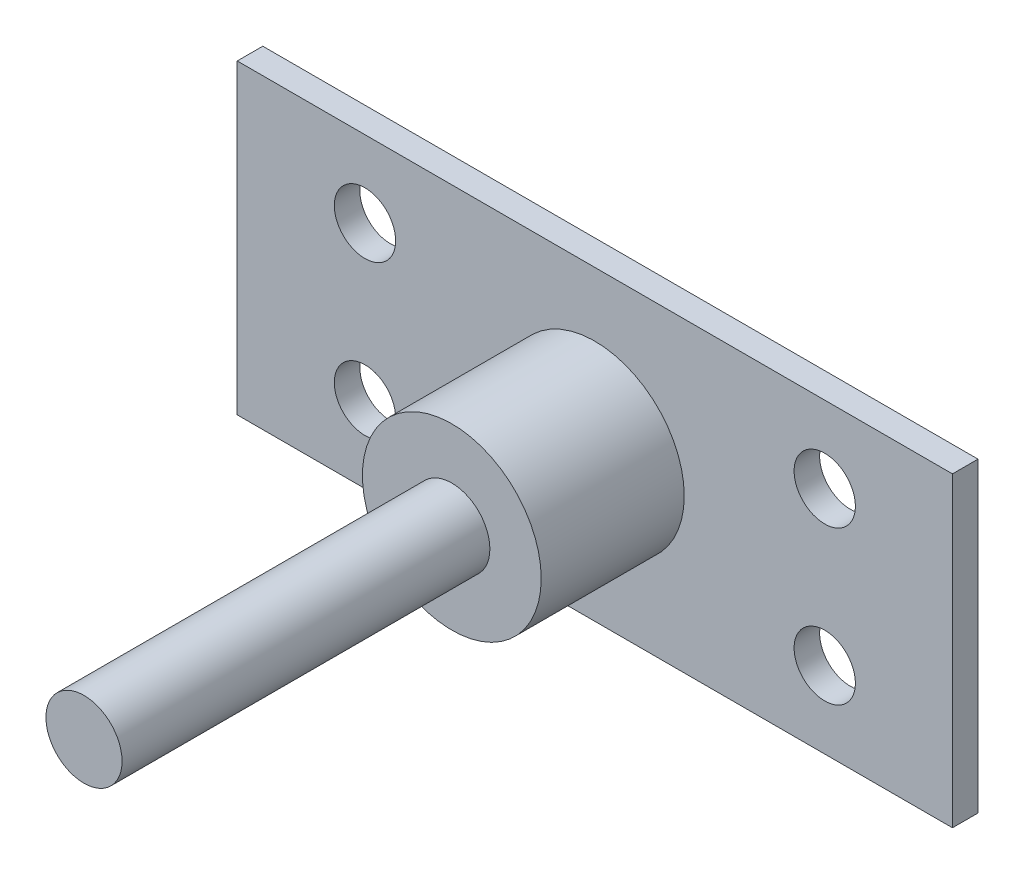
SolidWorks part; units mm, degrees
ref_plane "Front Plane" through (0, 0, 0) normal (0, 0, 1) x (1, 0, 0)
ref_plane "Top Plane" through (0, 0, 0) normal (0, 1, 0) x (1, 0, 0)
ref_plane "Right Plane" through (0, 0, 0) normal (1, 0, 0) x (0, 0, -1)
sketch "Sketch1" plane through (0, 0, 0) normal (0, 0, 1) x (1, 0, 0)
  line L1 (-70, 30) -> (70, 30)
  line L2 (-70, 30) -> (-70, -30)
  line L3 (-70, -30) -> (70, -30)
  line L4 (70, 30) -> (70, -30)
  line L5 (-70, 30) -> (70, -30) construction
  line L6 (-70, -30) -> (70, 30) construction
  point P0 (0, 0)
  dimension "D1" = 140
  dimension "D2" = 60
extrude "Boss-Extrude1" add sketch "Sketch1" along normal blind 5
sketch "Sketch2" plane through (0, 0, 5) normal (0, 0, 1) x (1, 0, 0)
  line L0 (70, 30) -> (-70, 30) construction
  line L1 (-45, 15) -> (45, 15) construction
  line L2 (-45, -15) -> (45, -15) construction
  line L3 (-70, -30) -> (70, -30) construction
  line L4 (0, 30) -> (0, -30) construction
  circle A0 centre (0, 0) radius 7.45
  circle A1 centre (-45, 15) radius 6
  circle A2 centre (45, 15) radius 6
  circle A3 centre (-45, -15) radius 6
  circle A4 centre (45, -15) radius 6
  point P17 (0, 15)
  point P18 (0, -15)
  dimension "D1" = 14.9
  dimension "D2" = 12
  dimension "D3" = 12
  dimension "D4" = 15
  dimension "D5" = 12
  dimension "D6" = 15
  dimension "D7" = 12
  dimension "D8" = 15
  dimension "D9" = 15
  dimension "D10" = 45
  dimension "D11" = 45
extrude "Cut-Extrude1" cut sketch "Sketch2" against normal blind 5
sketch "Sketch3" plane through (0, 0, 5) normal (0, 0, 1) x (1, 0, 0)
  circle A0 centre (0, 0) radius 7.45
extrude "Boss-Extrude3" add sketch "Sketch3" along normal blind 100 and the other way blind 5
sketch "Sketch4" plane through (0, 0, 5) normal (0, 0, 1) x (1, 0, 0)
  circle A0 centre (0, 0) radius 17.5
  dimension "D1" = 35
extrude "Boss-Extrude4" add sketch "Sketch4" along normal blind 28
